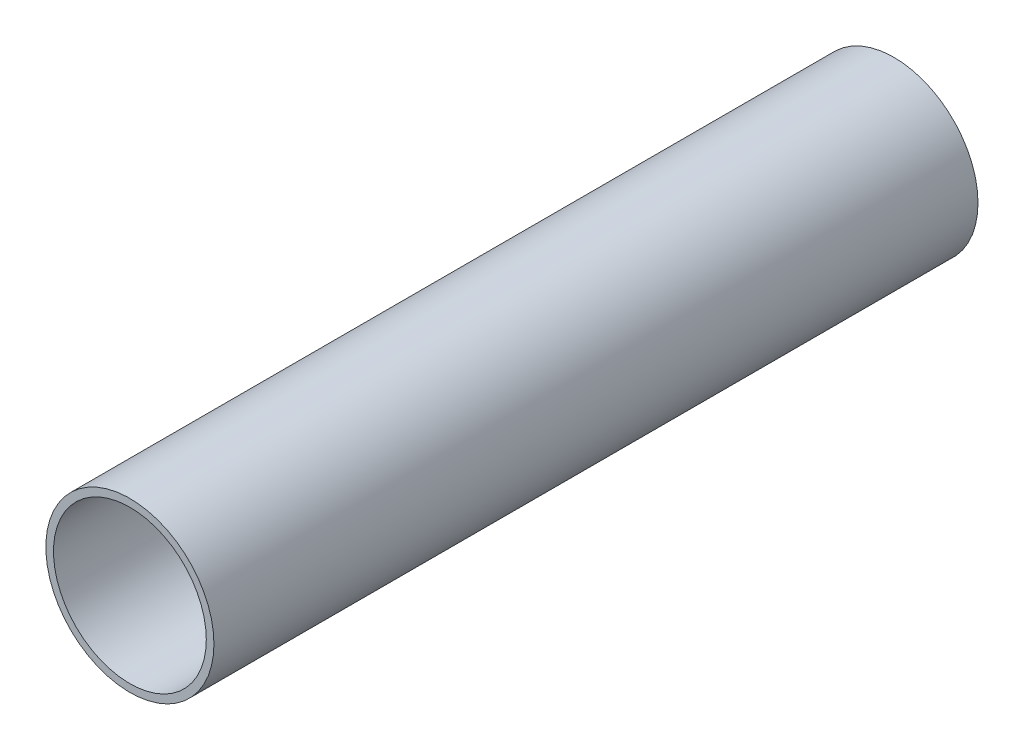
SolidWorks part; units mm, degrees
ref_plane "정면" through (0, 0, 0) normal (0, 0, 1) x (1, 0, 0)
ref_plane "윗면" through (0, 0, 0) normal (0, 1, 0) x (1, 0, 0)
ref_plane "우측면" through (0, 0, 0) normal (1, 0, 0) x (0, 0, -1)
sketch "스케치1" plane through (0, 0, 0) normal (0, 0, 1) x (1, 0, 0)
  circle A0 centre (0, 0) radius 11
  circle A1 centre (0, 0) radius 10
  dimension "D1" = 22
  dimension "D2" = 20
extrude "보스-돌출1" add sketch "스케치1" along normal blind 100
